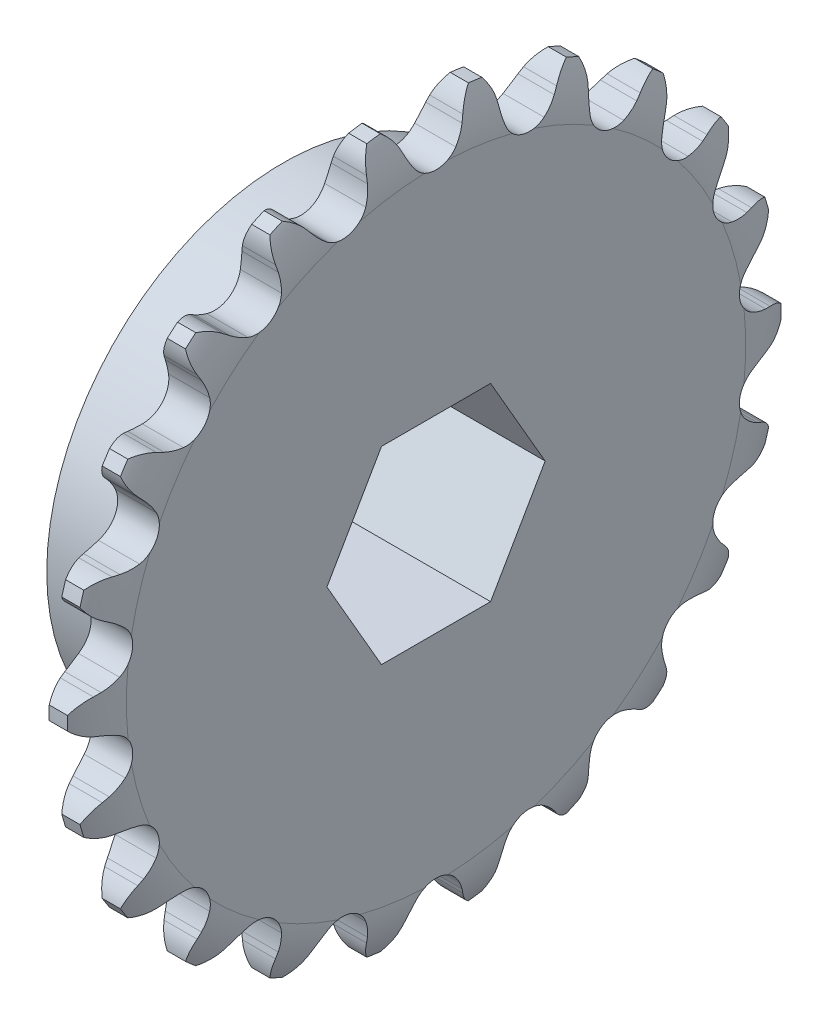
SolidWorks part; units mm, degrees
ref_plane "Plane1" through (0, 0, 0) normal (0, 0, 1) x (1, 0, 0)
ref_plane "Plane2" through (0, 0, 0) normal (0, 1, 0) x (1, 0, 0)
ref_plane "Plane3" through (0, 0, 0) normal (1, 0, 0) x (0, 0, -1)
sketch "Clipboard" plane through (0, 0, 0) normal (0, 1, 0) x (1, 0, 0)
  line L0 (0, 0) -> (5.8876, -2.3788)
  line L1 (-15, 0) -> (100, 0) construction
  line L2 (0, 0) -> (-0.5218, 0.5897)
  line L3 (0, 0) -> (-2.9658, 1.1335)
  line L4 (0, 0) -> (2.9438, 1.1894)
  line L5 (0, 0) -> (-9.6384, -3.5949)
  line L6 (0, 0) -> (-2.3214, -1.5662)
  line L7 (-0.5218, 0.5897) -> (8.9475, 4.6092)
  line L8 (-76.2, 38.1) -> (-65.4837, 38.1)
  line L9 (-73.2057, 38.5609) -> (-73.0533, 38.5634)
  line L10 (-73.0533, 76.1892) -> (-66.6525, 76.1892)
  circle A0 centre (0, 0) radius 1.651
  circle A1 centre (0, 0) radius 15.875
  circle A2 centre (0, 0) radius 15.875
  dimension "Dr" = 3.302
  dimension "MHD" = 31.75
  dimension "Hub_dia" = 31.75
  dimension "Num_teeth" = 22
  dimension "Pitch" = 6.35
  dimension "Width" = 3.175
  dimension "Chamfer_wid" = 0.7874
  dimension "Chamfer_dep" = 3.175
  dimension "Overall_len" = 10.287
  dimension "Show_teeth" = 22
  dimension "Thickness" = 2.8004
  dimension "OAL" = 10.2871
  dimension "T_dim" = 10.7163
  dimension "Width_const" = 0.1524
  dimension "Width_factor" = 0.93
  dimension "Num_strands" = 1
  dimension "Transv_pitch" = 6.4008
sketch "BasProSke" plane through (0, 0, 0) normal (0, 1, 0) x (1, 0, 0)
  line L0 (-10, 0) -> (60, 0) construction
  line L1 (0, 0) -> (0, 20.8126)
  line L2 (0, 0) -> (2.8004, 0)
  line L3 (2.8004, 0) -> (2.8003, 20.8126)
  line L4 (2.0129, 23.9876) -> (0.7874, 23.9876)
  arc A0 (0, 20.8126) -> (0.7874, 23.9876) centre (6.7949, 20.8126) cw
  arc A1 (2.8003, 20.8126) -> (2.0129, 23.9876) centre (-3.9946, 20.8126) ccw
  dimension "D1" = 6.7949
  dimension "G1" = 0.7874
  dimension "G2" = 0.7874
  dimension "H2" = 3.175
  dimension "Diameter" = 47.9752
  dimension "H1" = 3.175
  dimension "Thickness" = 2.8004
revolve "Base-Revolve" add sketch "BasProSke" angle 360 about L0
sketch "GrvSke" plane through (0, 0, 0) normal (0, 1, 0) x (1, 0, 0)
  line L0 (2.8003, 20.8126) -> (2.8003, 18.5266)
  line L1 (2.8003, 18.5266) -> (6.4008, 18.5266)
  line L2 (6.4008, 18.5266) -> (6.4008, 20.8126)
  line L3 (2.0129, 23.9876) -> (7.1882, 23.9876)
  line L4 (4.6006, 0) -> (4.6006, 52.07) construction
  line L5 (-10, 0) -> (60, 0) construction
  line L6 (0, 0) -> (35.56, 0) construction
  arc A0 (6.4008, 20.8126) -> (7.1882, 23.9876) centre (13.1957, 20.8126) cw
  arc A1 (2.8003, 20.8126) -> (2.0129, 23.9876) centre (-3.9946, 20.8126) ccw
  dimension "Diameter" = 47.9752
  dimension "H1" = 3.175
  dimension "Grv_diam" = 37.0532
  dimension "Grv_width" = 3.6004
  dimension "Offset" = 4.6006
  dimension "G1" = 0.7874
revolve "Groove" [suppressed] cut sketch "GrvSke" angle 360 about L6
pattern_linear "Grooves" [suppressed]
sketch "TooCutSke" plane through (0, 0, 0) normal (1, 0, 0) x (0, 0, -1)
  line L0 (1.9259, 22.2816) -> (2.0857, 22.6717)
  line L1 (0, 0) -> (0, 107) construction
  line L2 (0, 22.3097) -> (-10, 22.3097) construction
  line L3 (-1.9259, 22.2816) -> (-2.0857, 22.6717)
  arc A0 (1.3425, 21.2711) -> (1.9259, 22.2816) centre (-2.0893, 23.9261) ccw
  arc A1 (1.3425, 21.2711) -> (-1.3425, 21.2711) centre (0, 22.3097) cw
  arc A2 (2.0857, 22.6717) -> (4.5757, 24.3426) centre (4.5757, 21.6518) cw
  arc A3 (-1.3425, 21.2711) -> (-1.9259, 22.2816) centre (2.0893, 23.9261) cw
  arc A4 (-2.0857, 22.6717) -> (-4.5757, 24.3426) centre (-4.5757, 21.6518) ccw
  arc A5 (4.5757, 24.3426) -> (-4.5757, 24.3426) centre (0, 0) ccw
  dimension "R" = 1.6974
  dimension "E" = 4.339
  dimension "F" = 2.6908
  dimension "Pitch_radius" = 22.3097
  dimension "W" = 4.5757
  dimension "V" = 0.6579
  dimension "A" = 37.727
  dimension "B" = 15.455
extrude "ToothCut" cut sketch "TooCutSke" along normal through all
pattern_circular "TeethCuts" count 22 every 16.364 about axis through (-10, 0, 0) along (1, 0, 0) of "ToothCut"
sketch "HubNeaOneSke" plane through (0, 0, 0) normal (-1, 0, 0) x (0, 0, 1)
  circle A0 centre (0, 0) radius 15.875
  dimension "Diameter" = 31.75
extrude "HubNearOne" add sketch "HubNeaOneSke" along normal blind 7.4867
sketch "HubNeaBotSke" plane through (0, 0, 0) normal (-1, 0, 0) x (0, 0, 1)
  circle A0 centre (0, 0) radius 15.875
  dimension "Diameter" = 31.75
extrude "HubNearBoth" [suppressed] add sketch "HubNeaBotSke" along normal blind 3.7434
ref_plane "FarPln" through (2.8004, 0, 0) normal (1, 0, 0) x (0, 0, -1)
sketch "HubFarSke" plane through (2.8004, 0, 0) normal (1, 0, 0) x (0, 0, -1)
  circle A0 centre (0, 0) radius 15.875
  dimension "Diameter" = 31.75
extrude "HubFar" [suppressed] add sketch "HubFarSke" along normal blind 3.7434
sketch "BorSke" plane through (0, 0, 0) normal (1, 0, 0) x (0, 0, -1)
  circle A0 centre (0, 0) radius 4.7625
  dimension "Diameter" = 9.525
extrude "Bore" cut sketch "BorSke" along normal mid plane 20.5741
sketch "KeySke" plane through (0, 0, 0) normal (1, 0, 0) x (0, 0, -1)
  line L0 (-1.1913, 0) -> (-1.1913, 5.9538)
  line L1 (-1.1913, 5.9538) -> (1.1913, 5.9538)
  line L2 (1.1913, 5.9538) -> (1.1913, 0)
  line L3 (0, 0) -> (0, 34) construction
  line L4 (-1.1913, 0) -> (1.1913, 0)
  dimension "Offset" = 5.9538
  dimension "Width" = 2.3825
extrude "Keyway" [suppressed] cut sketch "KeySke" along normal mid plane 20.5741
pattern_circular "Keyway2" [suppressed] count 2 every 90 about axis through (-10, 0, 0) along (1, 0, 0)
sketch "Sketch1" plane through (-7.4867, 0, 0) normal (-1, 0, 0) x (0, 0, 1)
  line L1 (-7.3323, 0) -> (-3.6662, -6.35)
  line L2 (-3.6662, -6.35) -> (3.6662, -6.35)
  line L3 (3.6662, -6.35) -> (7.3323, 0)
  line L4 (7.3323, 0) -> (3.6662, 6.35)
  line L5 (3.6662, 6.35) -> (-3.6662, 6.35)
  line L6 (-3.6662, 6.35) -> (-7.3323, 0)
  circle A0 centre (0, 0) radius 6.35 construction
  dimension "D1" = 12.7
extrude "Cut-Extrude1" cut sketch "Sketch1" against normal through all
sketch "Sketch2" plane through (-7.4867, 0, 0) normal (-1, 0, 0) x (0, 0, 1)
  circle A0 centre (0, 0) radius 15.875
  circle A3 centre (0, 0) radius 15.875 construction
equation "\"Num_teeth@Clipboard\" = int( \"Num_teeth@Clipboard\" )"
equation "\"Num_teeth@Clipboard\" = ((sgn( \"Num_teeth@Clipboard\" - 5.0)+1)*( \"Num_teeth@Clipboard\" - 5.0))/2 +5.0"
equation "\"Num_teeth@Clipboard\" = ((sgn( \"Num_teeth@Clipboard\" - 200.0)-1)*( \"Num_teeth@Clipboard\" - 200.0))/-2 +200.0"
equation "\"MHD@Clipboard\" = \"Pitch@Clipboard\" * (1.0 / tan(3.14159265 / \"Num_teeth@Clipboard\" ) - 1.0) - 0.03"
equation "\"Thickness@Clipboard\"  = \"Width@Clipboard\" * \"Width_factor@Clipboard\" - \"Width_const@Clipboard\" + (\"Num_strands@Clipboard\" - 1) * \"Transv_pitch@Clipboard\""
equation "\"OAL@Clipboard\" = \"Thickness@Clipboard\""
equation "\"MHD@Clipboard\" = ((sgn( \"MHD@Clipboard\" - \"Hub_dia@Clipboard\" )-1)*( \"MHD@Clipboard\" - \"Hub_dia@Clipboard\" ))/-2+ \"Hub_dia@Clipboard\""
equation "\"OAL@Clipboard\" = ((sgn( \"OAL@Clipboard\" - \"Overall_len@Clipboard\" )+1)*( \"OAL@Clipboard\" - \"Overall_len@Clipboard\" ))/2 + \"Overall_len@Clipboard\" + 0.000002"
equation "\"Num_teeth@TeethCuts\" = int( \"Show_teeth@Clipboard\" ) + 1"
equation "\"Num_teeth@TeethCuts\" = ((sgn( \"Num_teeth@TeethCuts\" - \"Num_teeth@Clipboard\" )-1)*( \"Num_teeth@TeethCuts\" - \"Num_teeth@Clipboard\" ))/-2+ \"Num_teeth@Clipboard\""
equation "\"Num_teeth@TeethCuts\" = ((sgn( \"Num_teeth@TeethCuts\" - 2.0)+1)*( \"Num_teeth@TeethCuts\" - 2.0))/2 +2.0"
equation "\"Angle@TeethCuts\" = 360.0 / \"Num_teeth@Clipboard\""
equation "\"Pitch_radius@TooCutSke\" = ( \"Pitch@Clipboard\" / 2.0) / sin(3.14159265 / \"Num_teeth@Clipboard\" )  'ma"
equation "\"R@TooCutSke\"  = \"Dr@Clipboard\" * 0.5025 + 0.0015"
equation "\"A@TooCutSke\" = 35.0 + (60.0 / \"Num_teeth@Clipboard\")"
equation "\"E@TooCutSke\"  = \"Dr@Clipboard\" * 1.3025 + 0.0015"
equation "\"B@TooCutSke\"  = 18.0 - (56.0 / \"Num_teeth@Clipboard\" )"
equation "\"W@TooCutSke\" = 1.4 * \"Dr@Clipboard\" * cos(3.14159265 / \"Num_teeth@Clipboard\" )"
equation "\"V@TooCutSke\" = 1.4 * \"Dr@Clipboard\" * sin(3.14159265 / \"Num_teeth@Clipboard\" )"
equation "\"Diameter@BasProSke\" = 2.0 * ( (0.3 * \"Pitch@Clipboard\" ) +  \"Pitch@Clipboard\" / 2.0 / tan(3.14159265 / \"Num_teeth@Clipboard\" ))"
equation "\"Thickness@BasProSke\"  = \"Thickness@Clipboard\""
equation "\"G1@BasProSke\" =  \"Chamfer_wid@Clipboard\""
equation "\"G2@BasProSke\" =  \"Chamfer_wid@Clipboard\""
equation "\"H1@BasProSke\" =  \"Chamfer_dep@Clipboard\""
equation "\"H2@BasProSke\" =  \"Chamfer_dep@Clipboard\""
equation "\"Diameter@GrvSke\" = \"Diameter@BasProSke\""
equation "\"G1@GrvSke\" = \"Chamfer_wid@Clipboard\""
equation "\"H1@GrvSke\" = \"Chamfer_dep@Clipboard\""
equation "\"Grv_diam@GrvSke\" =  \"Pitch@Clipboard\" * (1.0 / tan(3.14159265 / \"Num_teeth@Clipboard\" ) - 1.0) - 0.03"
equation "\"Grv_width@GrvSke\" =  \"Transv_pitch@Clipboard\" - ( \"Width@Clipboard\" * \"Width_factor@Clipboard\" - \"Width_const@Clipboard\" )"
equation "\"Offset@GrvSke\" = \"Grv_width@GrvSke\" / 2.0 + ( \"Width@Clipboard\" * \"Width_factor@Clipboard\" - \"Width_const@Clipboard\" )"
equation "\"Offset@Grooves\" = \"Transv_pitch@Clipboard\""
equation "\"Num_grvs@Grooves\" = \"Num_strands@Clipboard\""
equation "\"Num_grvs@Grooves\" = \"Num_grvs@Grooves\" - 1 * sgn( \"Num_grvs@Grooves\" -1)"
equation "\"Diameter@HubNeaOneSke\" = \"MHD@Clipboard\""
equation "\"Length@HubNearOne\" = \"OAL@Clipboard\" - \"Thickness@BasProSke\""
equation "\"Diameter@HubNeaBotSke\" = \"MHD@Clipboard\""
equation "\"Length@HubNearBoth\" = ( \"OAL@Clipboard\" - \"Thickness@BasProSke\" ) / 2.0"
equation "\"Thickness@FarPln\" = \"Thickness@BasProSke\""
equation "\"Diameter@HubFarSke\" = \"MHD@Clipboard\""
equation "\"Length@HubFar\" = ( \"OAL@Clipboard\" - \"Thickness@BasProSke\" ) / 2.0"
equation "\"D1@Bore\" = \"OAL@Clipboard\" * 2.0"
equation "\"D1@Keyway\" = \"OAL@Clipboard\" * 2.0"
equation "\"Offset@KeySke\" = \"T_dim@Clipboard\" - \"Diameter@BorSke\" / 2.0"
